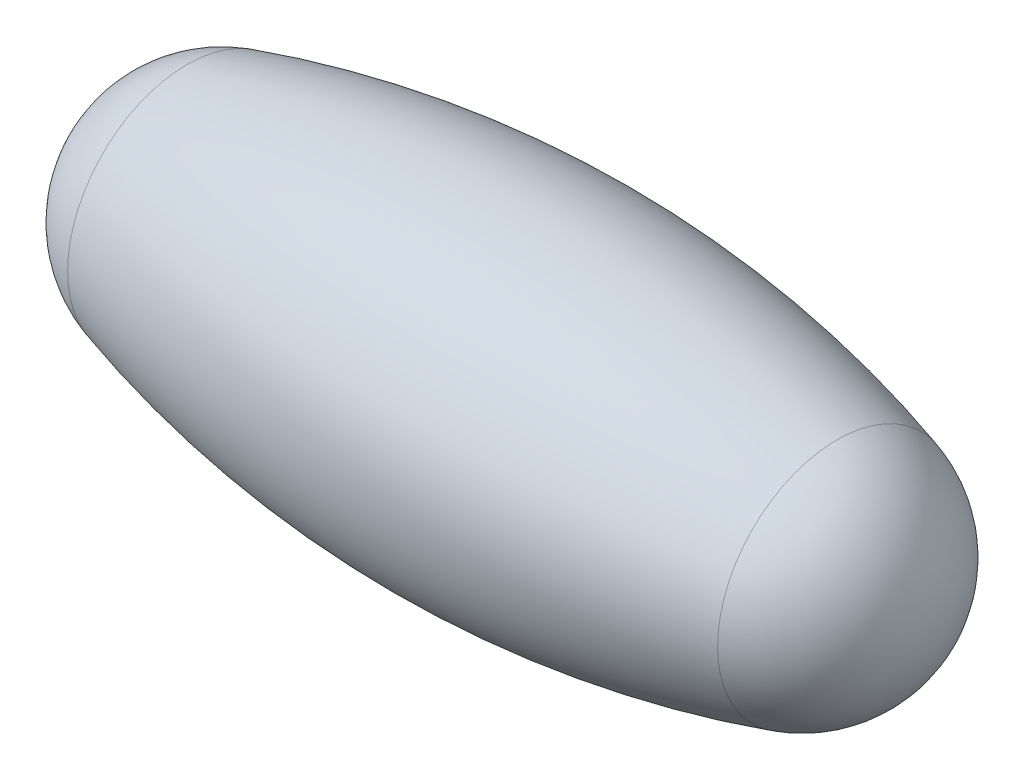
SolidWorks part; units mm, degrees
ref_plane "Front Plane" through (0, 0, 0) normal (0, 0, 1) x (1, 0, 0)
ref_plane "Top Plane" through (0, 0, 0) normal (0, 1, 0) x (1, 0, 0)
ref_plane "Right Plane" through (0, 0, 0) normal (1, 0, 0) x (0, 0, -1)
sketch "Sketch1" plane through (0, 0, 0) normal (0, 0, 1) x (1, 0, 0)
  line L0 (-63.5, 0) -> (63.5, 0)
  line L1 (0, 0) -> (0, 25.4) construction
  line L2 (-63.5, 0) -> (-63.5, 25.4) construction
  line L3 (-63.5, 25.4) -> (0, 25.4) construction
  arc A3 (-63.5, 0) -> (-49.784, 18.288) centre (-44.45, 0) cw
  arc A4 (-49.784, 18.288) -> (49.784, 18.288) centre (0, -152.4) cw
  arc A5 (63.5, 0) -> (49.784, 18.288) centre (44.45, 0) ccw
  point P4 (-101.6, 49.9364)
  point P9 (-73.9742, 36.632)
  point P13 (0, 49.7441)
  point P14 (0, 24.3042)
  dimension "D1" = 127
  dimension "D2" = 25.4
  dimension "D3" = 19.05
revolve "Revolve1" add sketch "Sketch1" angle 360 about L0
